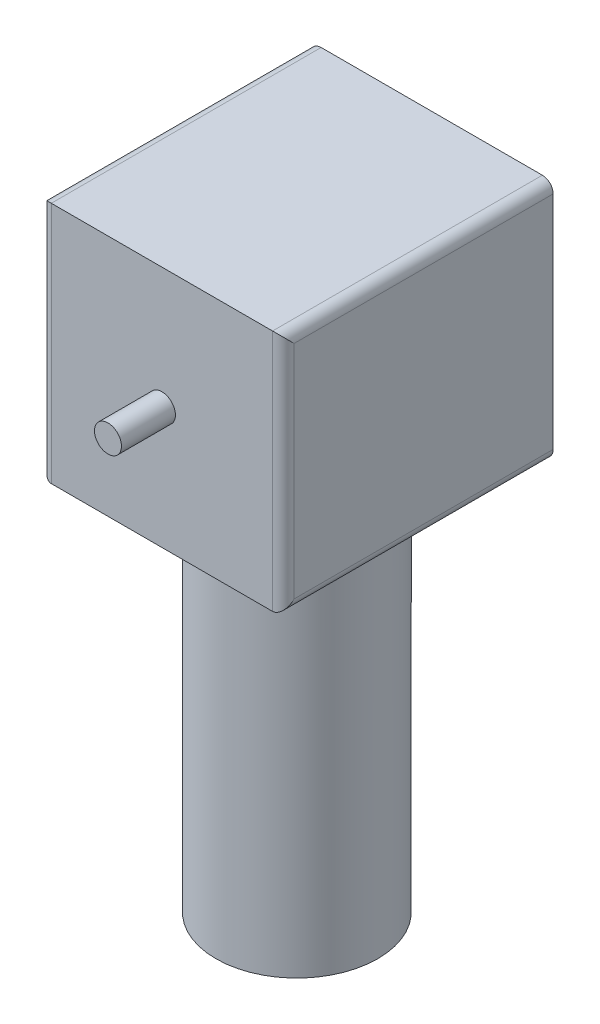
SolidWorks part; units mm, degrees
ref_plane "Front Plane" through (0, 0, 0) normal (0, 0, 1) x (1, 0, 0)
ref_plane "Top Plane" through (0, 0, 0) normal (0, 1, 0) x (1, 0, 0)
ref_plane "Right Plane" through (0, 0, 0) normal (1, 0, 0) x (0, 0, -1)
sketch "Sketch1" plane through (0, 0, 0) normal (0, 0, 1) x (1, 0, 0)
  line L1 (-22.5, 22.5) -> (22.5, 22.5)
  line L2 (-22.5, 22.5) -> (-22.5, -22.5)
  line L3 (-22.5, -22.5) -> (22.5, -22.5)
  line L4 (22.5, 22.5) -> (22.5, -22.5)
  line L5 (-22.5, 22.5) -> (22.5, -22.5) construction
  line L6 (-22.5, -22.5) -> (22.5, 22.5) construction
  point P0 (0, 0)
  dimension "D1" = 45
  dimension "D2" = 45
extrude "Boss-Extrude1" add sketch "Sketch1" along normal blind 50
sketch "Sketch4" plane through (0, -22.5, 0) normal (0, -1, 0) x (1, 0, 0)
  line L0 (0, 50) -> (0, 0) construction
  line L1 (-22.5, 50) -> (22.5, 50) construction
  circle A0 centre (0, 25) radius 15
  dimension "D1" = 30
  dimension "D2" = 25
extrude "Boss-Extrude2" add sketch "Sketch4" along normal blind 71
fillet "Fillet1" radius 2 6 edges at (-22.5, 0, 50) (22.5, 0, 50) (22.5, -22.5, 25) (-22.5, -22.5, 25) (-22.5, 22.5, 25) (22.5, 22.5, 25)
fillet "Fillet2" radius 5 1 edges at (0, -22.5, 10)
sketch "Sketch5" plane through (0, 0, 50) normal (0, 0, 1) x (1, 0, 0)
  circle A0 centre (0, 0) radius 2.5
  dimension "D1" = 5
extrude "Boss-Extrude3" add sketch "Sketch5" along normal blind 10
sketch "Sketch6" plane through (0, 0, 0) normal (0, 0, -1) x (-1, 0, 0)
  circle A0 centre (0, 0) radius 2.5 construction
  circle A1 centre (0, 0) radius 2.5
extrude "Boss-Extrude4" add sketch "Sketch6" along normal blind 10
sketch "Sketch7" plane through (0, -93.5, 0) normal (0, -1, 0) x (1, 0, 0)
  point P0 (0, 25)
